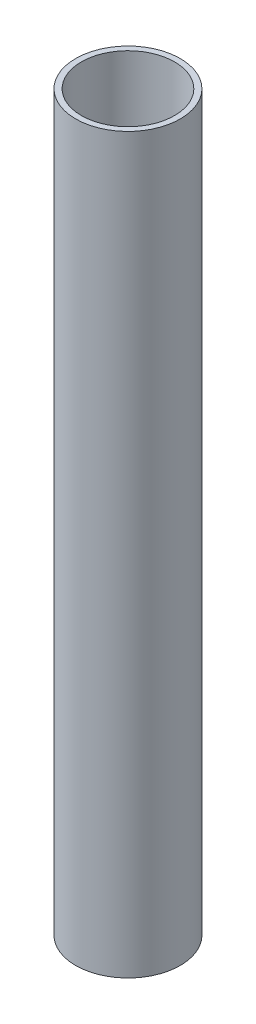
SolidWorks part; units mm, degrees
ref_plane "Front Plane" through (0, 0, 0) normal (0, 0, 1) x (1, 0, 0)
ref_plane "Top Plane" through (0, 0, 0) normal (0, 1, 0) x (1, 0, 0)
ref_plane "Right Plane" through (0, 0, 0) normal (1, 0, 0) x (0, 0, -1)
sketch "Sketch1" plane through (0, 0, 0) normal (0, 1, 0) x (1, 0, 0)
  circle A0 centre (0, 0) radius 14.5
  circle A1 centre (0, 0) radius 12.9125
  dimension "D1" = 29
  dimension "D2" = 1.5875
extrude "Boss-Extrude1" add sketch "Sketch1" along normal mid plane 203.2
